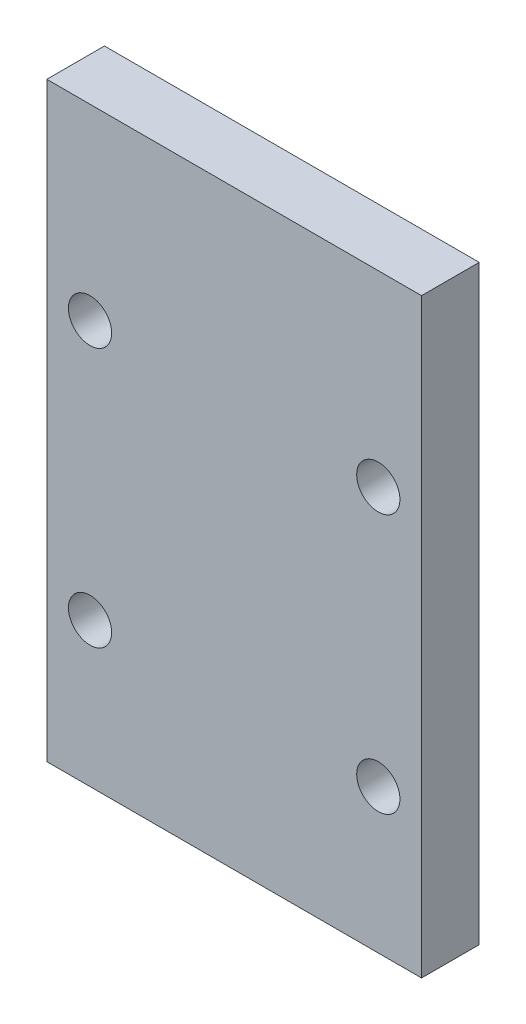
SolidWorks part; units mm, degrees
ref_plane "Front Plane" through (0, 0, 0) normal (0, 0, 1) x (1, 0, 0)
ref_plane "Top Plane" through (0, 0, 0) normal (0, 1, 0) x (1, 0, 0)
ref_plane "Right Plane" through (0, 0, 0) normal (1, 0, 0) x (0, 0, -1)
sketch "Sketch1" plane through (0, 0, 0) normal (0, 0, 1) x (1, 0, 0)
  line L8 (0, 0) -> (0, 41) construction
  line L9 (0, 41) -> (3.95, 41) construction
  line L10 (3.95, 41) -> (3.95, 31) construction
  line L11 (3.95, 31) -> (10.3, 31) construction
  line L12 (10.3, 31) -> (10.3, 9) construction
  line L13 (10.3, 9) -> (8.55, 9) construction
  line L14 (8.55, 9) -> (8.55, 4) construction
  line L15 (8.55, 4) -> (13, 4) construction
  line L16 (13, 4) -> (13, 0) construction
  line L17 (13, 0) -> (0, 0) construction
  line L18 (0, 0) -> (0, 41)
  line L19 (0, 41) -> (26, 41)
  line L20 (26, 41) -> (26, 0)
  line L21 (26, 0) -> (0, 0)
  line L22 (3, 41) -> (3, 0) construction
  line L23 (13, 41) -> (13, 0) construction
  circle A1 centre (3, 28) radius 1.5
  circle A2 centre (3, 10) radius 1.5
  circle A3 centre (23, 10) radius 1.5
  circle A4 centre (23, 28) radius 1.5
  dimension "D13" = 3
  dimension "D15" = 10
  dimension "D1" = 10
  dimension "D2" = 41
  dimension "D3" = 4
  dimension "D4" = 10.3
  dimension "D5" = 13
  dimension "D6" = 9.05
  dimension "D7" = 5
  dimension "D8" = 1.75
  dimension "D9" = 26
  dimension "D14" = 3
  dimension "D16" = 13
extrude "Boss-Extrude1" add sketch "Sketch1" along normal blind 4
